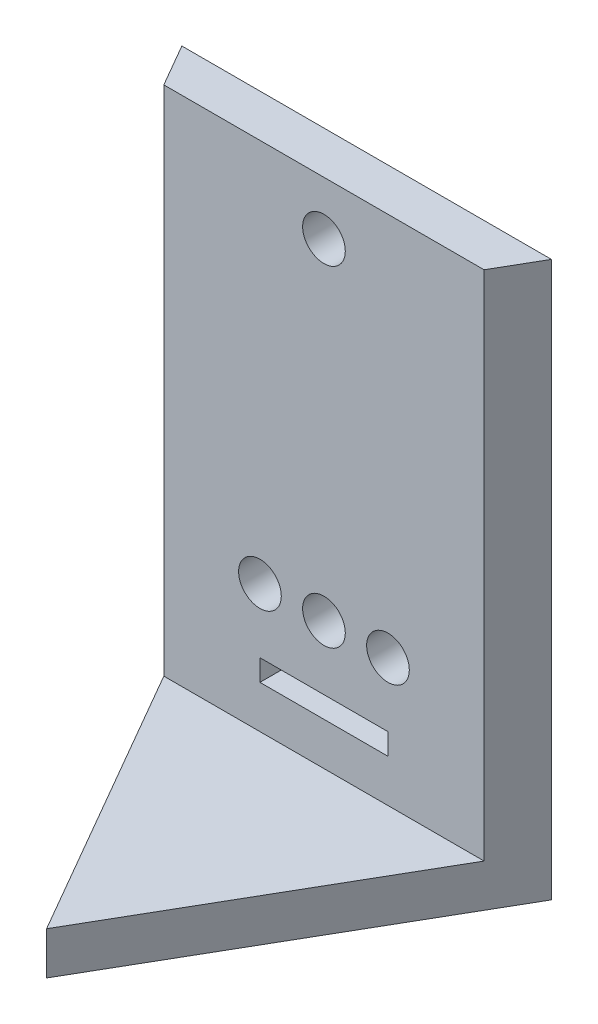
SolidWorks part; units mm, degrees
ref_plane "Front" through (0, 0, 0) normal (0, 0, 1) x (1, 0, 0)
ref_plane "Top" through (0, 0, 0) normal (0, 1, 0) x (1, 0, 0)
ref_plane "Right" through (0, 0, 0) normal (1, 0, 0) x (0, 0, -1)
sketch "Sketch1" plane through (0, 0, 0) normal (0, 1, 0) x (1, 0, 0)
  line L1 (86.6025, 0) -> (43.3013, 75)
  line L2 (43.3013, 75) -> (-43.3013, 75)
  line L3 (-43.3013, 75) -> (-86.6025, 0)
  line L4 (-86.6025, 0) -> (-43.3013, -75)
  line L5 (-43.3013, -75) -> (43.3013, -75)
  line L6 (43.3013, -75) -> (86.6025, 0)
  circle A0 centre (0, 0) radius 75 construction
  dimension "D1" = 150
extrude "Main Frame" add sketch "Sketch1" along normal blind 130
shell "Shell1" thickness 10
sketch "Sketch2" plane through (0, 130, 0) normal (0, 1, 0) x (1, 0, 0)
  line L0 (-43.3013, 75) -> (0, 0)
  line L1 (86.6025, 0) -> (43.3013, 75)
  line L2 (43.3013, 75) -> (-43.3013, 75) construction
  line L3 (-43.3013, 75) -> (-86.6025, 0)
  line L4 (-86.6025, 0) -> (-43.3013, -75)
  line L5 (-43.3013, -75) -> (43.3013, -75)
  line L6 (43.3013, -75) -> (86.6025, 0)
  line L7 (0, 0) -> (43.3013, 75)
  circle A0 centre (0, 0) radius 75 construction
extrude "Cut-Extrude1" cut sketch "Sketch2" against normal through all
sketch "Sketch5" plane through (0, 0, -75) normal (0, 0, -1) x (-1, 0, 0)
  line L0 (0, 40) -> (0, 130) construction
  line L1 (-43.3013, 130) -> (43.3013, 130) construction
  line L2 (0, 40) -> (0, 0) construction
  line L3 (-43.3013, 0) -> (43.3013, 0) construction
  line L4 (-15, 20) -> (15, 20)
  line L5 (-15, 20) -> (-15, 25)
  line L6 (-15, 25) -> (15, 25)
  line L7 (15, 20) -> (15, 25)
  line L8 (-15, 20) -> (15, 25) construction
  line L9 (-15, 25) -> (15, 20) construction
  circle A0 centre (-15, 40) radius 5
  circle A1 centre (0, 40) radius 5
  circle A2 centre (15, 40) radius 5
  circle A3 centre (0, 117.5) radius 5
  point P14 (0, 22.5)
  dimension "D1" = 10
  dimension "D2" = 10
  dimension "D3" = 5
  dimension "D4" = 30
  dimension "D5" = 20
  dimension "D6" = 12.5
extrude "External Ports" cut sketch "Sketch5" against normal up to next
ref_plane "Plane1" through (10, 0, 0) normal (1, 0, 0) x (0, 0, -1)
sketch "Sketch6" plane through (10, 0, 0) normal (1, 0, 0) x (0, 0, -1)
  line L0 (75, 110) -> (77, 110)
  line L1 (75, 130) -> (75, 0) construction
  line L2 (80, 107) -> (80, 88)
  line L3 (77, 85) -> (75, 85)
  line L4 (75, 130) -> (65, 130) construction
  arc A0 (80, 88) -> (77, 85) centre (77, 88) cw
  arc A1 (77, 110) -> (80, 107) centre (77, 107) cw
  point P8 (80, 85)
  point P11 (80, 110)
  dimension "D3" = 3
  dimension "D1" = 25
  dimension "D2" = 5
  dimension "D4" = 20
sketch "Sketch7" plane through (0, 0, -75) normal (0, 0, -1) x (-1, 0, 0)
  circle A0 centre (-10, 110) radius 1.25
  dimension "D1" = 2.5
sweep "Boom Mount" add profiles "Sketch7" path "Sketch6"
mirror "Mirror1" about plane through (0, 0, 0) normal (1, 0, 0) of "Boom Mount"
